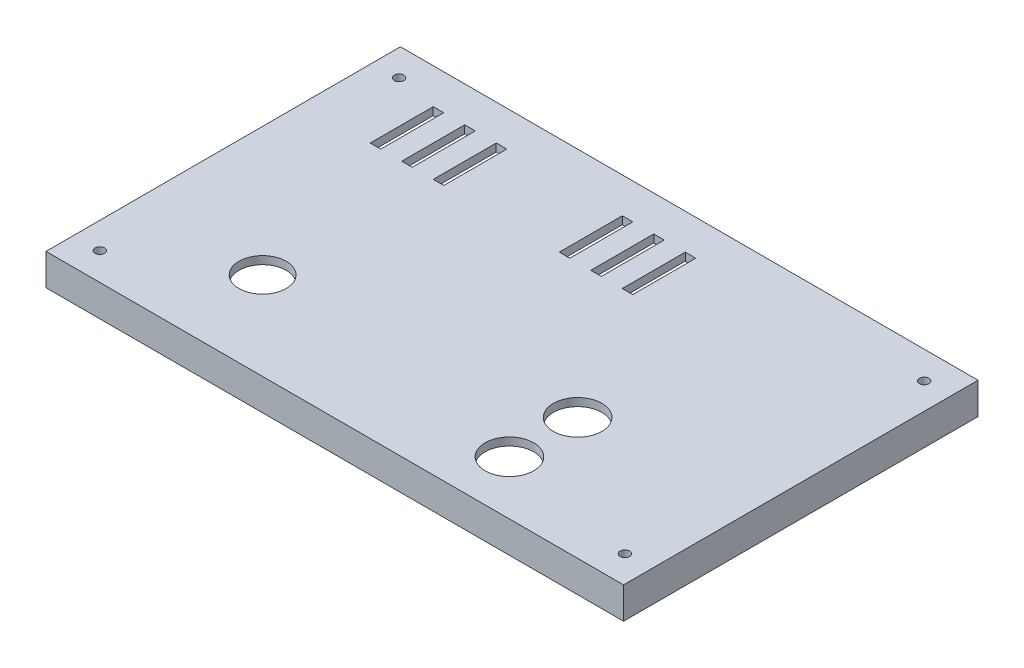
SolidWorks part; units mm, degrees
ref_plane "前视基准面" through (0, 0, 0) normal (0, 0, 1) x (1, 0, 0)
ref_plane "上视基准面" through (0, 0, 0) normal (0, 1, 0) x (1, 0, 0)
ref_plane "右视基准面" through (0, 0, 0) normal (1, 0, 0) x (0, 0, -1)
other "Configuration Table"
sketch "草图1" plane through (0, 0, 0) normal (0, 1, 0) x (1, 0, 0)
  line L1 (-110, -67.5) -> (110, -67.5)
  line L2 (-110, -67.5) -> (-110, 67.5)
  line L3 (-110, 67.5) -> (110, 67.5)
  line L4 (110, -67.5) -> (110, 67.5)
extrude "Lid_Top_3mm" add sketch "草图1" against normal blind 3
sketch "草图2" plane through (0, 0, 0) normal (0, 1, 0) x (1, 0, 0)
  line L0 (110, 67.5) -> (-110, 67.5) construction
  line L1 (-108, 65.5) -> (108, 65.5)
  line L2 (-108, 65.5) -> (-108, 67.5)
  line L3 (-108, 67.5) -> (108, 67.5)
  line L4 (108, 65.5) -> (108, 67.5)
extrude "Lid_Rim_Back" add sketch "草图2" against normal blind 12
sketch "草图3" plane through (0, 0, 0) normal (0, 1, 0) x (1, 0, 0)
  line L0 (-110, -67.5) -> (110, -67.5) construction
  line L1 (-108, -67.5) -> (108, -67.5)
  line L2 (-108, -67.5) -> (-108, -65.5)
  line L3 (-108, -65.5) -> (108, -65.5)
  line L4 (108, -67.5) -> (108, -65.5)
extrude "Lid_Rim_Front" add sketch "草图3" against normal blind 12
sketch "草图4" plane through (0, 0, 0) normal (0, 1, 0) x (1, 0, 0)
  line L1 (-110, -67.5) -> (-108, -67.5)
  line L2 (-110, -67.5) -> (-110, 67.5)
  line L3 (-110, 67.5) -> (-108, 67.5)
  line L4 (-108, -67.5) -> (-108, 67.5)
extrude "Lid_Rim_Left" add sketch "草图4" against normal blind 12
sketch "草图5" plane through (0, 0, 0) normal (0, 1, 0) x (1, 0, 0)
  line L0 (-110, -67.5) -> (110, -67.5) construction
  line L1 (108, -67.5) -> (110, -67.5)
  line L2 (108, -67.5) -> (108, 67.5)
  line L3 (108, 67.5) -> (110, 67.5)
  line L4 (110, -67.5) -> (110, 67.5)
extrude "Lid_Rim_Right" add sketch "草图5" against normal blind 12
sketch "草图6" plane through (0, 0, 0) normal (0, 1, 0) x (1, 0, 0)
  circle A0 centre (-100, -57) radius 1.8
extrude "Lid_Screw_Clearance_1" cut sketch "草图6" against normal blind 16
sketch "草图7" plane through (0, 0, 0) normal (0, 1, 0) x (1, 0, 0)
  circle A0 centre (100, -57) radius 1.8
extrude "Lid_Screw_Clearance_2" cut sketch "草图7" against normal blind 16
sketch "草图8" plane through (0, 0, 0) normal (0, 1, 0) x (1, 0, 0)
  circle A0 centre (-100, 57) radius 1.8
extrude "Lid_Screw_Clearance_3" cut sketch "草图8" against normal blind 16
sketch "草图9" plane through (0, 0, 0) normal (0, 1, 0) x (1, 0, 0)
  circle A0 centre (100, 57) radius 1.8
extrude "Lid_Screw_Clearance_4" cut sketch "草图9" against normal blind 16
sketch "草图10" plane through (0, 0, 0) normal (0, 1, 0) x (1, 0, 0)
  circle A0 centre (-61, -34) radius 9
extrude "OV5647_Lens_Opening_D18" cut sketch "草图10" against normal blind 4
sketch "草图11" plane through (0, 0, 0) normal (0, 1, 0) x (1, 0, 0)
  circle A0 centre (46, -47) radius 9.25
extrude "HC_SR04_Acoustic_Opening_1" cut sketch "草图11" against normal blind 4
sketch "草图12" plane through (0, 0, 0) normal (0, 1, 0) x (1, 0, 0)
  circle A0 centre (46, -21) radius 9.25
extrude "HC_SR04_Acoustic_Opening_2" cut sketch "草图12" against normal blind 4
sketch "草图13" plane through (0, 0, 0) normal (0, 1, 0) x (1, 0, 0)
  line L1 (-84, 30) -> (-80, 30)
  line L2 (-84, 30) -> (-84, 54)
  line L3 (-84, 54) -> (-80, 54)
  line L4 (-80, 30) -> (-80, 54)
extrude "Vent_Slot_1" cut sketch "草图13" against normal blind 4
sketch "草图14" plane through (0, 0, 0) normal (0, 1, 0) x (1, 0, 0)
  line L1 (-72, 30) -> (-68, 30)
  line L2 (-72, 30) -> (-72, 54)
  line L3 (-72, 54) -> (-68, 54)
  line L4 (-68, 30) -> (-68, 54)
extrude "Vent_Slot_2" cut sketch "草图14" against normal blind 4
sketch "草图15" plane through (0, 0, 0) normal (0, 1, 0) x (1, 0, 0)
  line L1 (-60, 30) -> (-56, 30)
  line L2 (-60, 30) -> (-60, 54)
  line L3 (-60, 54) -> (-56, 54)
  line L4 (-56, 30) -> (-56, 54)
extrude "Vent_Slot_3" cut sketch "草图15" against normal blind 4
sketch "草图16" plane through (0, 0, 0) normal (0, 1, 0) x (1, 0, 0)
  line L1 (-12, 30) -> (-8, 30)
  line L2 (-12, 30) -> (-12, 54)
  line L3 (-12, 54) -> (-8, 54)
  line L4 (-8, 30) -> (-8, 54)
extrude "Vent_Slot_4" cut sketch "草图16" against normal blind 4
sketch "草图17" plane through (0, 0, 0) normal (0, 1, 0) x (1, 0, 0)
  line L1 (0, 30) -> (4, 30)
  line L2 (0, 30) -> (0, 54)
  line L3 (0, 54) -> (4, 54)
  line L4 (4, 30) -> (4, 54)
extrude "Vent_Slot_5" cut sketch "草图17" against normal blind 4
sketch "草图18" plane through (0, 0, 0) normal (0, 1, 0) x (1, 0, 0)
  line L1 (12, 30) -> (16, 30)
  line L2 (12, 30) -> (12, 54)
  line L3 (12, 54) -> (16, 54)
  line L4 (16, 30) -> (16, 54)
extrude "Vent_Slot_6" cut sketch "草图18" against normal blind 4
